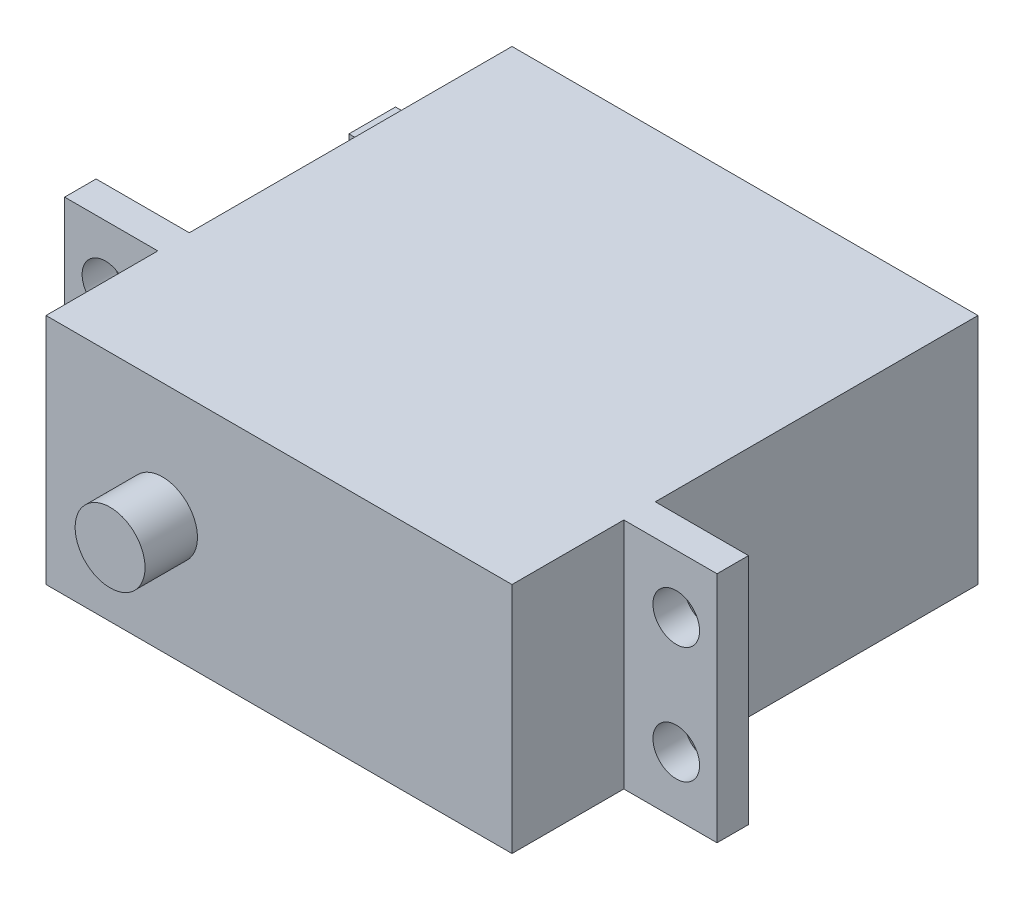
SolidWorks part; units mm, degrees
ref_plane "前视基准面" through (0, 0, 0) normal (0, 0, 1) x (1, 0, 0)
ref_plane "上视基准面" through (0, 0, 0) normal (0, 1, 0) x (1, 0, 0)
ref_plane "右视基准面" through (0, 0, 0) normal (1, 0, 0) x (0, 0, -1)
other "Configuration Table"
sketch "草图1" plane through (0, 0, 0) normal (0, 1, 0) x (1, 0, 0)
  line L1 (0, 0) -> (40, 0)
  line L2 (0, 0) -> (0, 40)
  line L3 (0, 40) -> (40, 40)
  line L4 (40, 0) -> (40, 40)
  dimension "D1" = 40
  dimension "D2" = 40
extrude "凸台-拉伸1" add sketch "草图1" along normal blind 20
sketch "草图2" plane through (0, 0, 0) normal (0, 0, 1) x (1, 0, 0)
  line L0 (0, 10) -> (10, 10)
  line L1 (0, 20) -> (0, 0) construction
  circle A0 centre (10, 10) radius 3
  dimension "D2" = 6
  dimension "D1" = 10
extrude "凸台-拉伸2" add sketch "草图2" along normal blind 4.5
ref_plane "基准面1" through (0, 0, -12.3) normal (0, 0, -1) x (-1, 0, 0)
sketch "草图4" plane through (0, 0, -12.3) normal (0, 0, -1) x (-1, 0, 0)
  line L0 (-1040, 10) -> (48960, 10) construction
  line L1 (-40, 20) -> (-48, 20)
  line L2 (-40, 20) -> (-40, 0)
  line L3 (-40, 0) -> (-48, 0)
  line L4 (-48, 20) -> (-48, 0)
  line L5 (-40, 20) -> (-44.5, 20)
  line L6 (-40, 20) -> (-40, 15)
  line L7 (-40, 15) -> (-44.5, 15)
  line L8 (-44.5, 20) -> (-44.5, 15)
  line L9 (-20, -980) -> (-20, 49020) construction
  line L10 (-40, 20) -> (0, 20) construction
  line L11 (0, 20) -> (0, 0)
  line L12 (0, 0) -> (8, 0)
  line L13 (8, 20) -> (8, 0)
  line L14 (0, 20) -> (8, 20)
  circle A0 centre (-44.5, 15) radius 2
  circle A1 centre (-44.5, 5) radius 2
  circle A2 centre (4.5, 5) radius 2
  circle A3 centre (4.5, 15) radius 2
  point P11 (-40, 10)
  point P19 (-20, 20)
  dimension "D5" = 4
  dimension "D1" = 20
  dimension "D2" = 8
  dimension "D3" = 4.5
  dimension "D4" = 5
extrude "凸台-拉伸4" add sketch "草图4" against normal blind 2.7 contours A0 L8 L1 L4 L3 L2 L7 A1 | A0 L7 L2 L1 L8 | L14 L11 L12 L13 A2 A3
sketch "草图5" plane through (0, 0, 0) normal (-1, 0, 0) x (0, 0, 1)
  line L0 (-40, 10) -> (-35, 10)
  line L1 (-40, 20) -> (-40, 0) construction
  line L3 (-37, 6.5) -> (-33, 6.5)
  line L4 (-37, 6.5) -> (-37, 13.5)
  line L5 (-37, 13.5) -> (-33, 13.5)
  line L6 (-33, 6.5) -> (-33, 13.5)
  line L7 (-37, 6.5) -> (-33, 13.5) construction
  line L8 (-37, 13.5) -> (-33, 6.5) construction
  dimension "D1" = 5
  dimension "D2" = 4
  dimension "D3" = 7
extrude "凸台-拉伸5" add sketch "草图5" along normal blind 7
